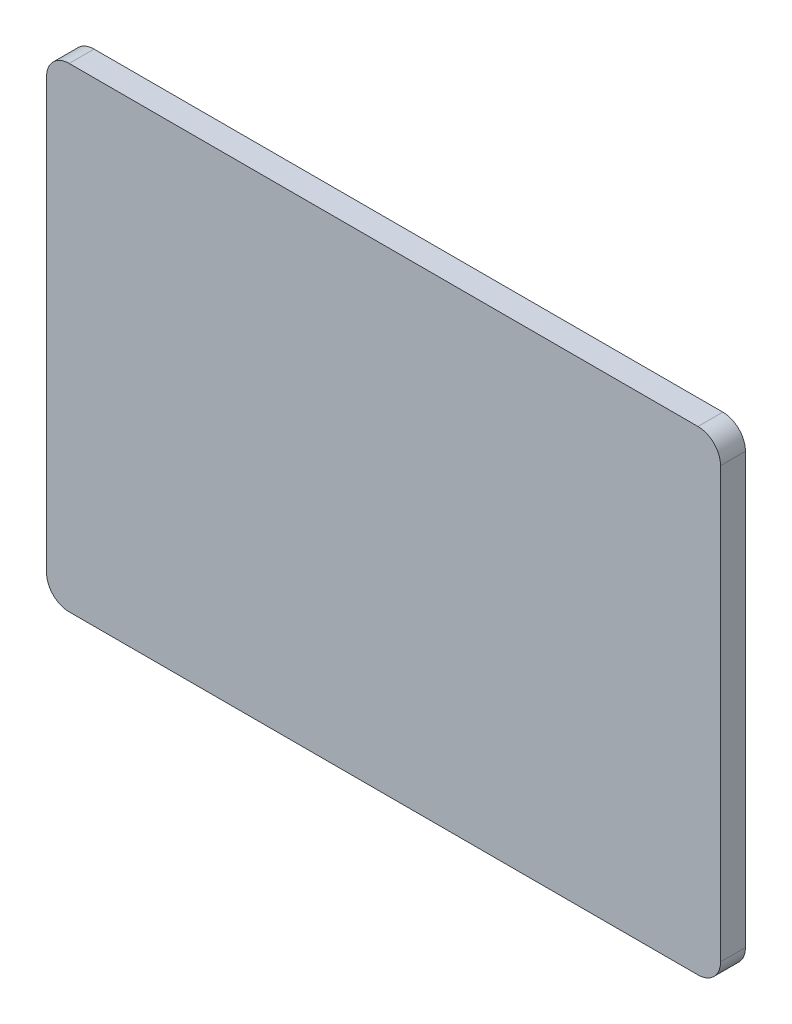
SolidWorks part; units mm, degrees
ref_plane "Plan de face" through (0, 0, 0) normal (0, 0, 1) x (1, 0, 0)
ref_plane "Plan de dessus" through (0, 0, 0) normal (0, 1, 0) x (1, 0, 0)
ref_plane "Plan de droite" through (0, 0, 0) normal (1, 0, 0) x (0, 0, -1)
sketch "Esquisse1" plane through (0, 0, 0) normal (0, 0, 1) x (1, 0, 0)
  line L1 (0, 0) -> (298, 0)
  line L2 (0, 0) -> (0, 210)
  line L3 (0, 210) -> (298, 210)
  line L4 (298, 0) -> (298, 210)
  dimension "D1" = 298
  dimension "D2" = 210
extrude "Boss.-Extru.1" add sketch "Esquisse1" along normal blind 11
fillet "Congé1" radius 10 4 edges at (298, 0, 5.5) (0, 0, 5.5) (0, 210, 5.5) (298, 210, 5.5)
